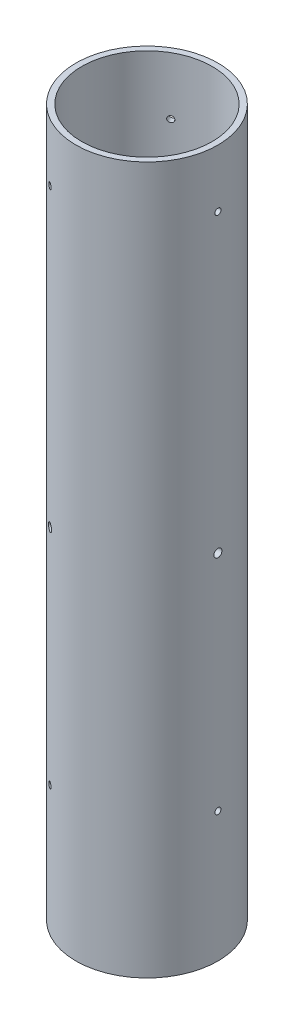
SolidWorks part; units mm, degrees
material "75 Degrees Custom Wound Fiberglass"
ref_plane "Front Plane" through (0, 0, 0) normal (0, 0, 1) x (1, 0, 0)
ref_plane "Top Plane" through (0, 0, 0) normal (0, 1, 0) x (1, 0, 0)
ref_plane "Right Plane" through (0, 0, 0) normal (1, 0, 0) x (0, 0, -1)
sketch "Sketch1" plane through (0, 0, 0) normal (0, 1, 0) x (1, 0, 0)
  circle A0 centre (0, 0) radius 38.227
  circle A1 centre (0, 0) radius 41.656
  dimension "D1" = 76.454
  dimension "D2" = 83.312
extrude "Boss-Extrude1" add sketch "Sketch1" along normal blind 414.3375
ref_axis "Axis1" through (0, -7.62, 0) along (0, 1, 0)
ref_plane "Plane1" through (-20.828, 0, 36.0752) normal (-0.5, 0, 0.866) x (0, -1, 0)
sketch "Sketch2" plane through (-20.828, 0, 36.0752) normal (-0.5, 0, 0.866) x (0, -1, 0)
  line L0 (7.62, 0) -> (-160.02, 0) construction
  line L2 (0, -41.656) -> (0, 41.656) construction
  circle A0 centre (-76.2, 0) radius 1.778
  dimension "D1" = 76.2
  dimension "D2" = 3.556
extrude "Cut-Extrude1" cut sketch "Sketch2" against normal up to next
pattern_circular "CirPattern1" count 3 over 360 about axis through (0, -7.62, 0) along (0, 1, 0) of "Cut-Extrude1"
ref_plane "Plane2" through (0, 207.1687, 0) normal (0, 1, 0) x (1, 0, 0)
sketch "Sketch3" plane through (-20.828, 0, 36.0752) normal (-0.5, 0, 0.866) x (0, -1, 0)
  line L0 (-207.1687, 43.5864) -> (-207.1687, -43.5864) construction
  circle A0 centre (-207.1687, 0) radius 2.3813
  dimension "D1" = 4.7625
extrude "Pressure Equalization Hole" cut sketch "Sketch3" against normal up to next
pattern_circular "CirPattern2" count 3 over 360 about axis through (0, -7.62, 0) along (0, 1, 0) of "Pressure Equalization Hole"
ref_plane "Plane3" through (41.656, 0, 0) normal (1, 0, 0) x (0, 0, -1)
sketch "Sketch4" plane through (41.656, 0, 0) normal (-1, 0, 0) x (0, -1, 0)
  line L0 (-414.3375, 41.656) -> (-414.3375, -41.656) construction
  circle A0 centre (-380.5301, 0) radius 1.7859
  dimension "D1" = 3.5719
  dimension "D2" = 33.8074
extrude "Cut-Extrude3" cut sketch "Sketch4" along normal up to next
pattern_circular "CirPattern3" count 3 over 360 about axis through (0, -7.62, 0) along (0, 1, 0) of "Cut-Extrude3"
equation "\"D2@Sketch1\"=\"D1@Sketch1\"+0.135*2"
